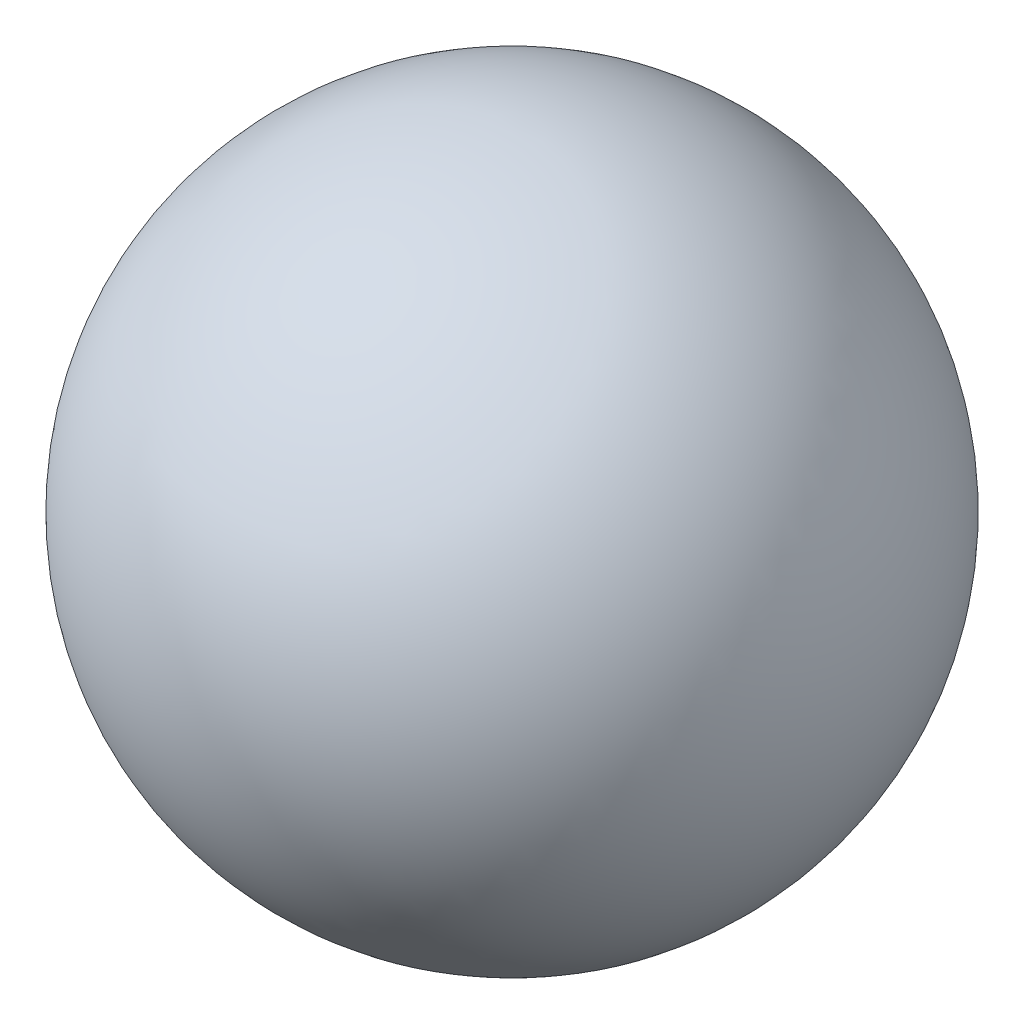
SolidWorks part; units mm, degrees
ref_plane "Front Plane" through (0, 0, 0) normal (0, 0, 1) x (1, 0, 0)
ref_plane "Top Plane" through (0, 0, 0) normal (0, 1, 0) x (1, 0, 0)
ref_plane "Right Plane" through (0, 0, 0) normal (1, 0, 0) x (0, 0, -1)
sketch "Sketch1" plane through (0, 0, 0) normal (0, 0, 1) x (1, 0, 0)
  line L0 (0, 1.75) -> (0, -1.75)
  arc A0 (0, 1.75) -> (0, -1.75) centre (0, 0) ccw
  dimension "D1" = 3.5
revolve "Revolve1" add sketch "Sketch1" angle 360 about L0
